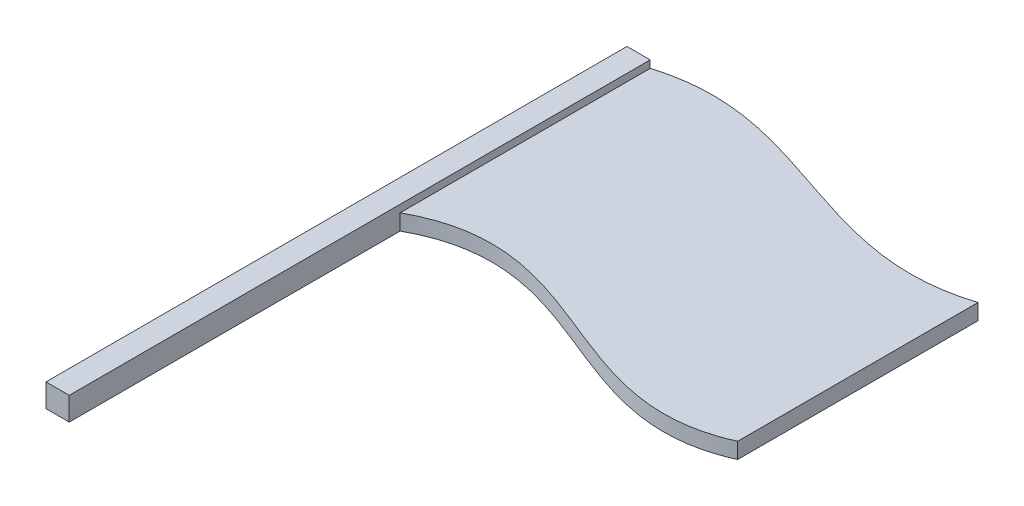
SolidWorks part; units mm, degrees
ref_plane "Front Plane" through (0, 0, 0) normal (0, 0, 1) x (1, 0, 0)
ref_plane "Top Plane" through (0, 0, 0) normal (0, 1, 0) x (1, 0, 0)
ref_plane "Right Plane" through (0, 0, 0) normal (1, 0, 0) x (0, 0, -1)
sketch "Sketch1" plane through (0, 0, 0) normal (0, 1, 0) x (1, 0, 0)
  line L1 (0, 0) -> (2.2, 0)
  line L2 (0, 0) -> (0, 55)
  line L3 (0, 55) -> (2.2, 55)
  line L4 (2.2, 0) -> (2.2, 55)
  line L5 (0, 0) -> (2.2, 55) construction
  line L6 (0, 55) -> (2.2, 0) construction
  point P4 (1.1, 27.5)
  dimension "D1" = 2.2
  dimension "D2" = 55
extrude "Boss-Extrude1" add sketch "Sketch1" along normal blind 2.2
sketch "Sketch2" plane through (0, 0, 0) normal (0, 1, 0) x (1, 0, 0)
  line L0 (2.2, 0) -> (2.2, 55) construction
  line L1 (36.9062, 51.3261) -> (36.9062, 28.5717)
  line L2 (2.2, 0) -> (2.2, 55) construction
  line L3 (2.2, 55) -> (2.2, 31.3231)
  spline S0 degree 3 poles (2.2, 55) (14.2965, 58.7638) (24.5058, 47.3439) (36.9062, 51.3261) knots 0 0 0 0 1 1 1 1
  spline S1 degree 3 poles (2.2, 31.3231) (14.5595, 38.154) (24.6569, 23.0363) (36.9062, 28.5717) knots 0 0 0 0 1 1 1 1
extrude "Boss-Extrude2" add sketch "Sketch2" along normal blind 1.5
